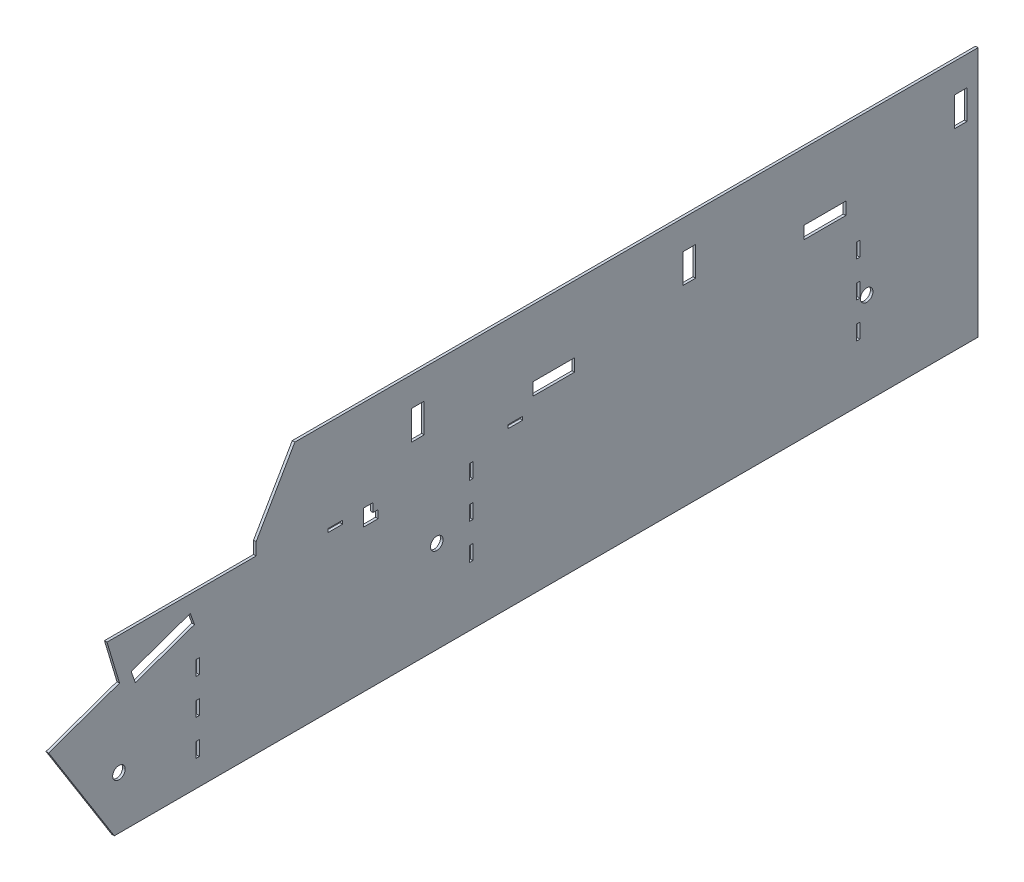
SolidWorks part; units mm, degrees
ref_plane "Front Plane" through (0, 0, 0) normal (0, 0, 1) x (1, 0, 0)
ref_plane "Top Plane" through (0, 0, 0) normal (0, 1, 0) x (1, 0, 0)
ref_plane "Right Plane" through (0, 0, 0) normal (1, 0, 0) x (0, 0, -1)
sketch "Sketch1" plane through (0, 0, 0) normal (1, 0, 0) x (0, 0, -1)
  line L0 (436.7463, 0.6594) -> (432.7463, 0.6594)
  line L1 (436.7463, 17.6594) -> (436.7463, 0.6594)
  line L2 (436.7463, 17.6594) -> (432.7463, 17.6594)
  line L3 (432.7463, 17.6594) -> (432.7463, 0.6594)
  line L4 (45.7084, 32.4461) -> (28.7084, 32.4461)
  line L5 (45.7084, 36.4461) -> (45.7084, 32.4461)
  line L6 (45.7084, 36.4461) -> (28.7084, 36.4461)
  line L7 (28.7084, 36.4461) -> (28.7084, 32.4461)
  line L8 (-408.1165, 7.0272) -> (-339.6566, 31.1916)
  line L9 (-403.2826, -6.6625) -> (-408.1165, 7.0272)
  line L10 (-334.8227, 17.4953) -> (-403.2826, -6.6625)
  line L11 (-339.6566, 31.1916) -> (-334.8227, 17.4953)
  line L12 (-82.8614, 74.8001) -> (-82.8614, 108.6774)
  line L13 (-68.3413, 74.8001) -> (-82.8614, 74.8001)
  line L14 (-68.3413, 108.6774) -> (-68.3413, 74.8001)
  line L15 (-82.8614, 108.6774) -> (-68.3413, 108.6774)
  line L16 (57.5001, 50.5906) -> (57.5001, 65.1173)
  line L17 (105.8991, 50.5906) -> (57.5001, 50.5906)
  line L18 (105.8991, 65.1173) -> (105.8991, 50.5906)
  line L19 (57.5001, 65.1173) -> (105.8991, 65.1173)
  line L20 (231.7405, 74.8001) -> (231.7405, 108.6774)
  line L21 (246.2606, 74.8001) -> (231.7405, 74.8001)
  line L22 (246.2606, 108.6774) -> (246.2606, 74.8001)
  line L23 (231.7405, 108.6774) -> (246.2606, 108.6774)
  line L24 (420.5127, 65.119) -> (420.5127, 50.5989)
  line L25 (372.1037, 65.119) -> (420.5127, 65.119)
  line L26 (372.1037, 50.5989) -> (372.1037, 65.119)
  line L27 (420.5127, 50.5989) -> (372.1037, 50.5989)
  line L28 (560.8625, 74.8001) -> (546.3424, 74.8001)
  line L29 (560.8625, 108.6774) -> (560.8625, 74.8001)
  line L30 (546.3424, 108.6774) -> (560.8625, 108.6774)
  line L31 (-503.9458, -26.8502) -> (-427.6871, -148.1709)
  line L32 (-421.6644, 2.1883) -> (-503.9458, -26.8502)
  line L33 (-436.1861, 50.5939) -> (-421.6644, 2.1883)
  line L34 (-263.2513, 50.6289) -> (-436.1861, 50.5939)
  line L35 (-263.2513, 65.0539) -> (-263.2513, 50.6289)
  line L36 (-218.3839, 142.5497) -> (-263.2513, 65.0539)
  line L37 (573.7687, 142.5497) -> (-218.3839, 142.5497)
  line L38 (573.7687, -148.1709) -> (573.7687, 142.5497)
  line L39 (-329.1886, -18.5339) -> (-333.1886, -18.5339)
  line L40 (-333.1886, -18.5339) -> (-333.1886, -35.5339)
  line L41 (-329.1886, -35.5339) -> (-333.1886, -35.5339)
  line L42 (-329.1886, -18.5339) -> (-329.1886, -35.5339)
  line L43 (-329.1886, -59.7207) -> (-333.1886, -59.7207)
  line L44 (-333.1886, -59.7207) -> (-333.1886, -76.6404)
  line L45 (-329.1886, -76.6404) -> (-333.1886, -76.6404)
  line L46 (-329.1886, -59.7207) -> (-329.1886, -76.6404)
  line L47 (-329.1886, -100.8272) -> (-333.1886, -100.8272)
  line L48 (-333.1886, -117.8272) -> (-333.1886, -100.8272)
  line L49 (-329.1886, -117.8272) -> (-333.1886, -117.8272)
  line L50 (-329.1886, -100.8272) -> (-329.1886, -117.8272)
  line L51 (-180.0395, 36.4461) -> (-180.0395, 32.4461)
  line L52 (-180.0395, 32.4461) -> (-163.0395, 32.4461)
  line L53 (-163.0395, 36.4461) -> (-163.0395, 32.4461)
  line L54 (-180.0395, 36.4461) -> (-163.0395, 36.4461)
  line L55 (-127.6656, 36.4461) -> (-127.6656, 26.4461)
  line L56 (-138.8528, 36.4461) -> (-127.6656, 36.4461)
  line L57 (-138.8528, 36.4461) -> (-138.8528, 17.3384)
  line L58 (-138.8528, 17.3384) -> (-121.933, 17.3384)
  line L59 (-121.933, 26.4461) -> (-121.933, 17.3384)
  line L60 (-127.6656, 26.4461) -> (-121.933, 26.4461)
  line L61 (-12, 19.7) -> (-16, 19.7)
  line L62 (-16, 19.7) -> (-16, 2.7)
  line L63 (-12, 2.7) -> (-16, 2.7)
  line L64 (-12, 19.7) -> (-12, 2.7)
  line L65 (-12, -21.4867) -> (-16, -21.4867)
  line L66 (-16, -21.4867) -> (-16, -38.4065)
  line L67 (-12, -38.4065) -> (-16, -38.4065)
  line L68 (-12, -21.4867) -> (-12, -38.4065)
  line L69 (-12, -62.5932) -> (-16, -62.5932)
  line L70 (-16, -79.5932) -> (-16, -62.5932)
  line L71 (-12, -79.5932) -> (-16, -79.5932)
  line L72 (-12, -62.5932) -> (-12, -79.5932)
  line L73 (436.7463, -23.5273) -> (432.7463, -23.5273)
  line L74 (432.7463, -23.5273) -> (432.7463, -40.4471)
  line L75 (436.7463, -40.4471) -> (432.7463, -40.4471)
  line L76 (436.7463, -23.5273) -> (436.7463, -40.4471)
  line L77 (436.7463, -64.6338) -> (432.7463, -64.6338)
  line L78 (432.7463, -81.6338) -> (432.7463, -64.6338)
  line L79 (436.7463, -81.6338) -> (432.7463, -81.6338)
  line L80 (436.7463, -64.6338) -> (436.7463, -81.6338)
  line L81 (546.3424, 74.8001) -> (546.3424, 108.6774)
  line L82 (573.7687, -148.1709) -> (-427.6871, -148.1709)
  spline S0 degree 3 poles (444.7022, -48.6335) (440.6903, -48.6335) (437.4421, -45.382) (437.4421, -41.3735) knots 0 0 0 0 0.333333 0.333333 0.333333 0.333333
  spline S1 degree 3 poles (437.4421, -41.3735) (437.4421, -37.3617) (440.6937, -34.1135) (444.7022, -34.1135) knots 0.333333 0.333333 0.333333 0.333333 1 1 1 1
  spline S2 degree 3 poles (444.7022, -34.1135) (448.7124, -34.1135) (451.9639, -37.3617) (451.9639, -41.3735) knots 0 0 0 0 0.333333 0.333333 0.333333 0.333333
  spline S3 degree 3 poles (451.9639, -41.3735) (451.9639, -45.372) (448.7124, -48.6335) (444.7022, -48.6335) knots 0.333333 0.333333 0.333333 0.333333 1 1 1 1
  spline S4 degree 3 poles (-53.8196, -48.6335) (-57.8298, -48.6335) (-61.0797, -45.382) (-61.0797, -41.3735) knots 0 0 0 0 0.333333 0.333333 0.333333 0.333333
  spline S5 degree 3 poles (-61.0797, -41.3735) (-61.0797, -37.3617) (-57.8282, -34.1135) (-53.8196, -34.1135) knots 0.333333 0.333333 0.333333 0.333333 1 1 1 1
  spline S6 degree 3 poles (-53.8196, -34.1135) (-49.8111, -34.1135) (-46.5596, -37.3617) (-46.5596, -41.3735) knots 0 0 0 0 0.333333 0.333333 0.333333 0.333333
  spline S7 degree 3 poles (-46.5596, -41.3735) (-46.5596, -45.372) (-49.8111, -48.6335) (-53.8196, -48.6335) knots 0.333333 0.333333 0.333333 0.333333 1 1 1 1
  spline S8 degree 3 poles (-422.3548, -94.6631) (-426.3633, -94.6631) (-429.6148, -91.4116) (-429.6148, -87.4031) knots 0 0 0 0 0.333333 0.333333 0.333333 0.333333
  spline S9 degree 3 poles (-429.6148, -87.4031) (-429.6148, -83.3946) (-426.3633, -80.1431) (-422.3548, -80.1431) knots 0.333333 0.333333 0.333333 0.333333 1 1 1 1
  spline S10 degree 3 poles (-422.3548, -80.1431) (-418.3462, -80.1431) (-415.0947, -83.3946) (-415.0947, -87.4031) knots 0 0 0 0 0.333333 0.333333 0.333333 0.333333
  spline S11 degree 3 poles (-415.0947, -87.4031) (-415.0947, -91.4116) (-418.3462, -94.6631) (-422.3548, -94.6631) knots 0.333333 0.333333 0.333333 0.333333 1 1 1 1
extrude "Boss-Extrude2" add sketch "Sketch1" along normal blind 3
